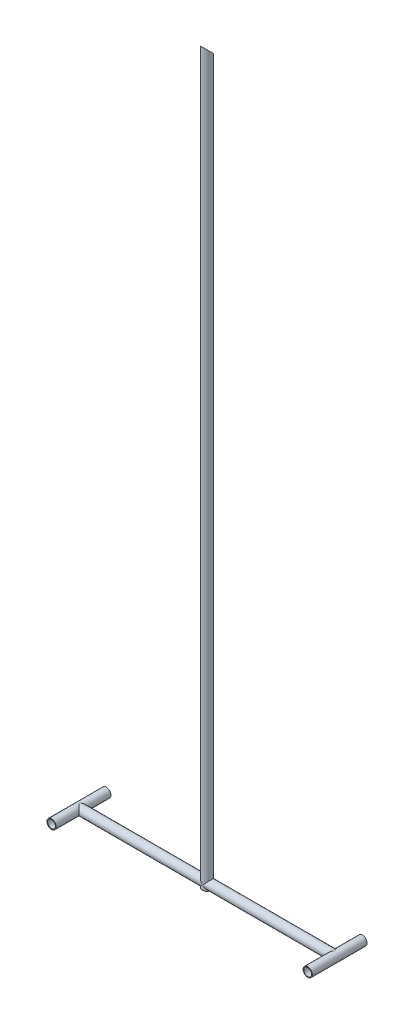
SolidWorks part; units mm, degrees
ref_plane "Front Plane" through (0, 0, 0) normal (0, 0, 1) x (1, 0, 0)
ref_plane "Top Plane" through (0, 0, 0) normal (0, 1, 0) x (1, 0, 0)
ref_plane "Right Plane" through (0, 0, 0) normal (1, 0, 0) x (0, 0, -1)
sketch "Sketch1" plane through (0, 0, 0) normal (0, 1, 0) x (1, 0, 0)
  circle A0 centre (0, 0) radius 12.7
  dimension "D1" = 25.4
extrude "Extrude-Thin1" add sketch "Sketch1" along normal blind 2000 thin thin type one direction reverse wall 2
sketch "Sketch6" plane through (0, 0, 0) normal (0, 0, 1) x (1, 0, 0)
  line L0 (-12.7, 0) -> (12.7, 0) construction
  circle A0 centre (350.8, 12.7) radius 12.7
  dimension "D1" = 25.4
  dimension "D2" = 350.8
extrude "Extrude-Thin4" add sketch "Sketch6" along normal mid plane 150 separate body thin thin type one direction reverse wall 2
sketch "Sketch7" plane through (0, 0, 0) normal (1, 0, 0) x (0, 0, -1)
  line L0 (-12.7, 0) -> (12.7, 0) construction
  circle A0 centre (0, 12.7) radius 12.7
  dimension "D1" = 25.4
extrude "Extrude-Thin5" add sketch "Sketch7" along normal up to surface and the other way up to surface from offset 50 thin up to face at (363.5, 12.7, 75) other way up to face at (0, 2000, 12.7) thin type one direction reverse wall 2
sketch "Sketch8" plane through (0, 0, 0) normal (0, 0, 1) x (1, 0, 0)
  line L0 (-12.7, 0) -> (12.7, 0) construction
  circle A0 centre (-350.8, 12.7) radius 12.7
  dimension "D1" = 25.4
  dimension "D2" = 350.8
extrude "Extrude-Thin6" add sketch "Sketch8" along normal mid plane 150 separate body thin thin type one direction reverse wall 2
sketch "Sketch9" plane through (0, 0, 0) normal (1, 0, 0) x (0, 0, -1)
  line L0 (-12.7, 0) -> (12.7, 0) construction
  circle A0 centre (0, 12.7) radius 12.7
  dimension "D1" = 25.4
extrude "Extrude-Thin8" add sketch "Sketch9" against normal up to surface and the other way up to surface from offset 50 thin up to face at (-338.1, 12.7, 75) other way up to face at (0, 2000, 12.7) thin type one direction reverse wall 2 offset against normal yes
sketch "Sketch10" plane through (0, 0, 0) normal (1, 0, 0) x (0, 0, -1)
  line L0 (-12.7, 2000) -> (12.7, 1974.6) construction
  line L1 (12.7, 12.7) -> (12.7, 2000) construction
  line L2 (10.7, 2000) -> (-10.7, 2000) construction
  dimension "D1" = 45
ref_plane "Plane2" through (0, 993.65, -993.65) normal (0, -0.7071, 0.7071) x (0, -0.7071, -0.7071)
other "SurfaceCut1"
